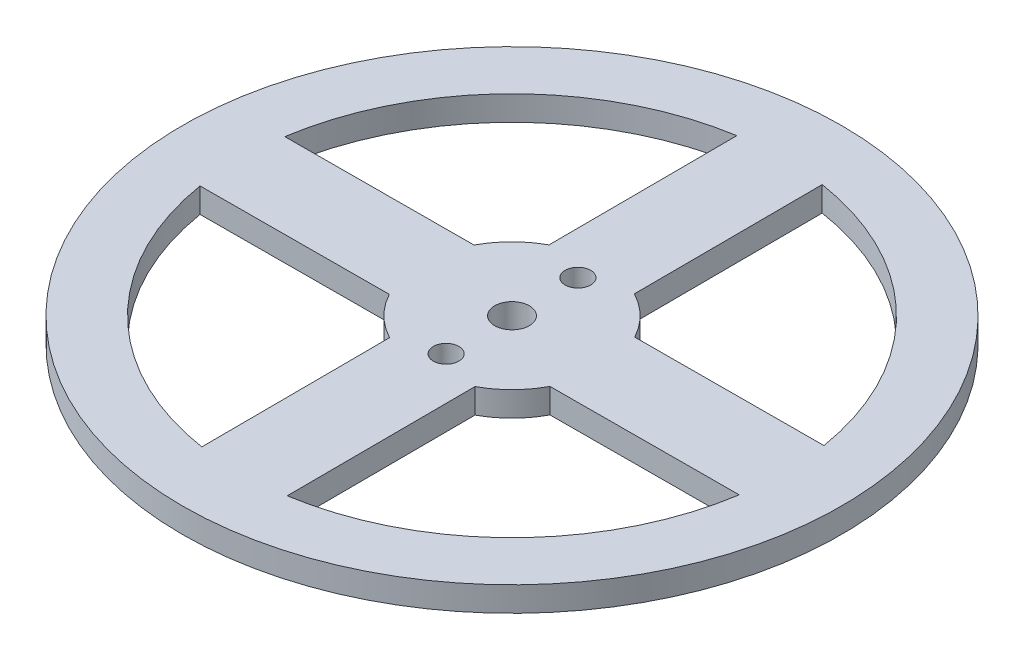
SolidWorks part; units mm, degrees
ref_plane "前视基准面" through (0, 0, 0) normal (0, 0, 1) x (1, 0, 0)
ref_plane "上视基准面" through (0, 0, 0) normal (0, 1, 0) x (1, 0, 0)
ref_plane "右视基准面" through (0, 0, 0) normal (1, 0, 0) x (0, 0, -1)
sketch "草图1" plane through (0, 0, 0) normal (0, 1, 0) x (1, 0, 0)
  circle A0 centre (0, 0) radius 6.2
  circle A1 centre (0, 0) radius 8
  circle A2 centre (0, 8) radius 1.55
  circle A3 centre (0, 0) radius 40
  circle A4 centre (0, -8) radius 1.55
extrude "凸台-拉伸1" add sketch "草图1" along normal blind 3 contours A3 A4 A1 A2 | A4 A1 A2 A0 | A0
sketch "草图4" plane through (0, 3, 0) normal (0, 1, 0) x (1, 0, 0)
  line L0 (-5.2862, 32.5739) -> (-5.0384, -32.6131)
  line L21 (5.0384, 32.6131) -> (5.2862, -32.5739)
  line L22 (32.5739, 5.2862) -> (-32.6131, 5.0384)
  line L23 (32.6131, -5.0384) -> (-32.5739, -5.2862)
  circle A0 centre (0, 0) radius 33
  circle A2 centre (0, 0) radius 11
sketch "草图5" plane through (0, 3, 0) normal (0, 1, 0) x (1, 0, 0)
  circle A0 centre (0, 0) radius 2.1
extrude "切除-拉伸4" cut sketch "草图5" against normal blind 10
extrude "切除-拉伸5" cut sketch "草图4" against normal blind 10 contours A2 L0 A0 L22 | A2 L22 A0 L21 | A2 L21 A0 L23 | A2 L23 A0 L0
